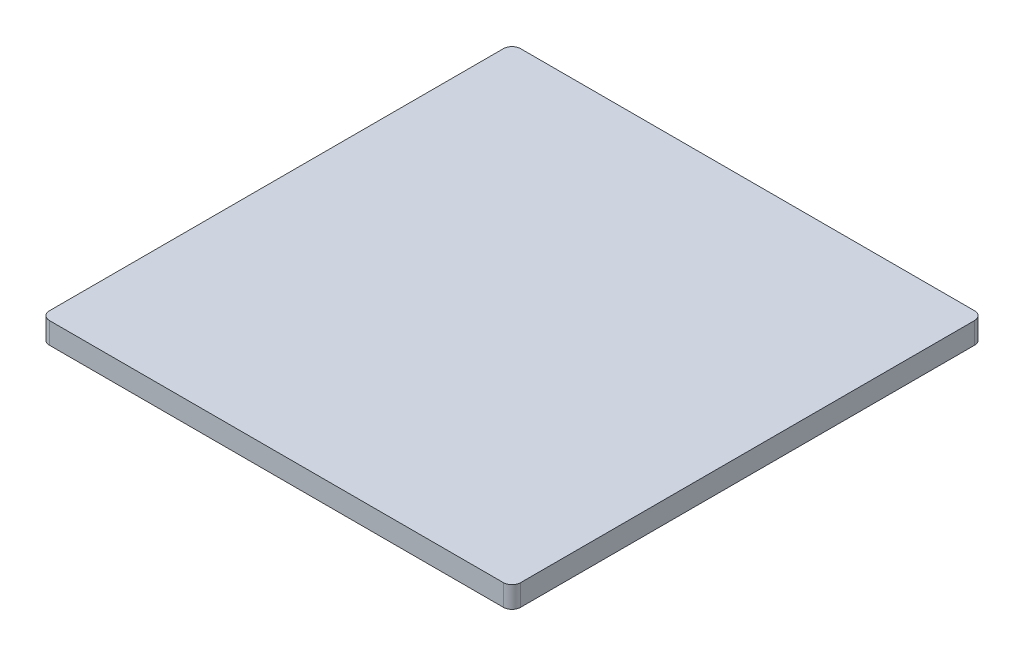
SolidWorks part; units mm, degrees
ref_plane "前视基准面" through (0, 0, 0) normal (0, 0, 1) x (1, 0, 0)
ref_plane "上视基准面" through (0, 0, 0) normal (0, 1, 0) x (1, 0, 0)
ref_plane "右视基准面" through (0, 0, 0) normal (1, 0, 0) x (0, 0, -1)
other "Configuration Table"
sketch "草图1" plane through (0, 0, 0) normal (0, 1, 0) x (1, 0, 0)
  line L1 (1, 0) -> (54, 0)
  line L2 (0, 1) -> (0, 54)
  line L3 (1, 55) -> (54, 55)
  line L4 (55, 1) -> (55, 54)
  arc A0 (54, 0) -> (55, 1) centre (54, 1) ccw
  arc A1 (1, 0) -> (0, 1) centre (1, 1) cw
  arc A2 (54, 55) -> (55, 54) centre (54, 54) cw
  arc A3 (0, 54) -> (1, 55) centre (1, 54) cw
  point P7 (55, 0)
  point P10 (0, 0)
  point P13 (55, 55)
  point P16 (0, 55)
  dimension "D3" = 1
  dimension "D1" = 55
  dimension "D2" = 55
extrude "凸台-拉伸1" add sketch "草图1" along normal blind 2.5
